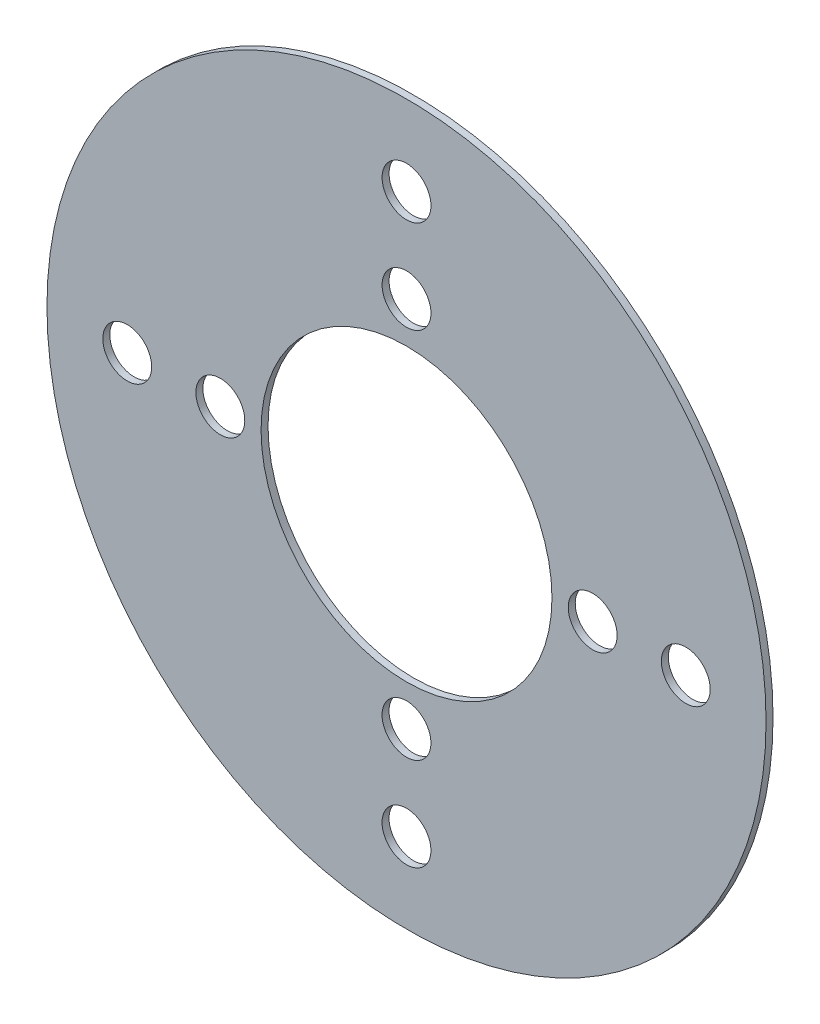
SolidWorks part; units mm, degrees
material "Alliage 6061"
ref_plane "Face" through (0, 0, 0) normal (0, 0, 1) x (1, 0, 0)
ref_plane "Dessus" through (0, 0, 0) normal (0, 1, 0) x (1, 0, 0)
ref_plane "Droite" through (0, 0, 0) normal (1, 0, 0) x (0, 0, -1)
sketch "Esquisse1" plane through (0, 0, 0) normal (0, 0, 1) x (1, 0, 0)
  circle A0 centre (0, 0) radius 30.9
  circle A1 centre (0, 0) radius 12.5
  dimension "D1" = 61.8
  dimension "D2" = 25
extrude "Boss.-Extru.1" add sketch "Esquisse1" along normal blind 0.6
sketch "Esquisse2" plane through (0, 0, 0.6) normal (0, 0, 1) x (1, 0, 0)
  line L0 (0, 0) -> (0, 30.9) construction
  circle A0 centre (0, 0) radius 16 construction
  circle A1 centre (0, 0) radius 24 construction
  circle A2 centre (0, 0) radius 30.9 construction
  circle A3 centre (0, 16) radius 2.1
  circle A4 centre (0, 24) radius 2.1
  dimension "D1" = 48
  dimension "D2" = 32
  dimension "D3" = 4.2
extrude "Enlèv. mat.-Extru.1" cut sketch "Esquisse2" against normal through all
pattern_circular "Répétition circulaire1" count 4 over 360 about axis through (0, 0, 0) along (0, 0, 1) of "Enlèv. mat.-Extru.1"
